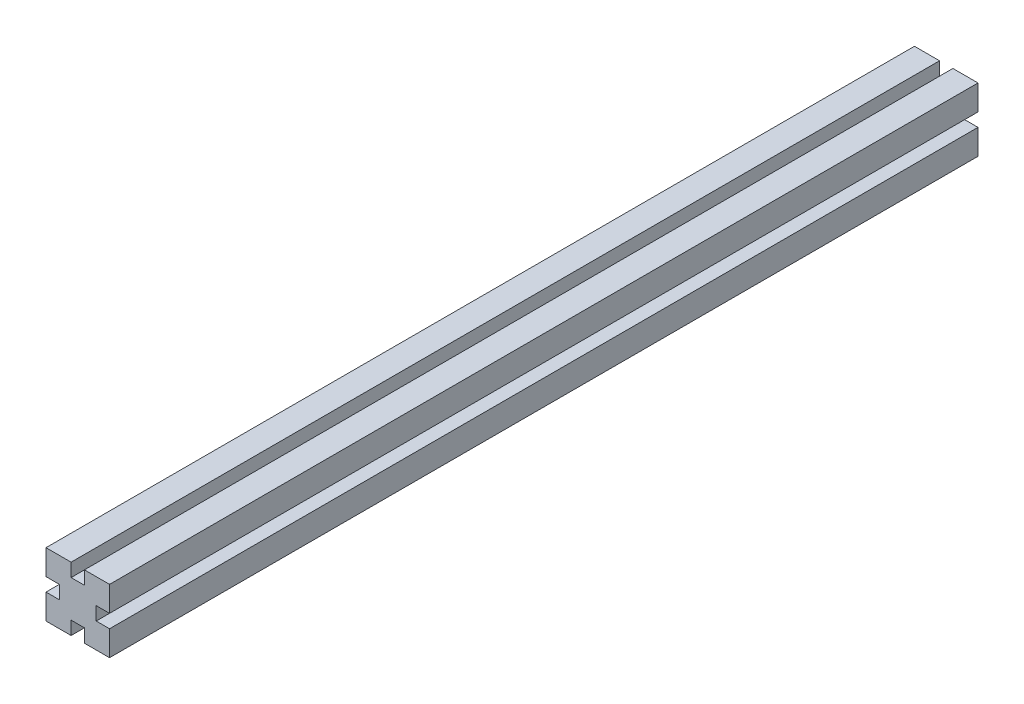
SolidWorks part; units mm, degrees
ref_plane "Front Plane" through (0, 0, 0) normal (0, 0, 1) x (1, 0, 0)
ref_plane "Top Plane" through (0, 0, 0) normal (0, 1, 0) x (1, 0, 0)
ref_plane "Right Plane" through (0, 0, 0) normal (1, 0, 0) x (0, 0, -1)
sketch "Sketch1" plane through (0, 0, 0) normal (0, 0, 1) x (1, 0, 0)
  line L0 (-19.05, -19.05) -> (-4, -19.05)
  line L1 (-4, -19.05) -> (-4, -11.05)
  line L2 (-4, -11.05) -> (4, -11.05)
  line L3 (4, -11.05) -> (4, -19.05)
  line L4 (4, -19.05) -> (19.05, -19.05)
  line L5 (19.05, -19.05) -> (19.05, -4)
  line L6 (19.05, -4) -> (11.05, -4)
  line L7 (11.05, -4) -> (11.05, 4)
  line L8 (11.05, 4) -> (19.05, 4)
  line L9 (19.05, 4) -> (19.05, 19.05)
  line L10 (19.05, 19.05) -> (4, 19.05)
  line L11 (4, 19.05) -> (4, 11.05)
  line L12 (4, 11.05) -> (-4, 11.05)
  line L13 (-4, 11.05) -> (-4, 19.05)
  line L14 (-4, 19.05) -> (-19.05, 19.05)
  line L15 (-19.05, 19.05) -> (-19.05, 4)
  line L16 (-19.05, 4) -> (-11.05, 4)
  line L17 (-11.05, 4) -> (-11.05, -4)
  line L18 (-11.05, -4) -> (-19.05, -4)
  line L19 (-19.05, -4) -> (-19.05, -19.05)
extrude "Profile" add sketch "Sketch1" along normal blind 520.7
equation "\"length\" = 520.7mm"
equation "\"D1@Profile\" = \"length\""
